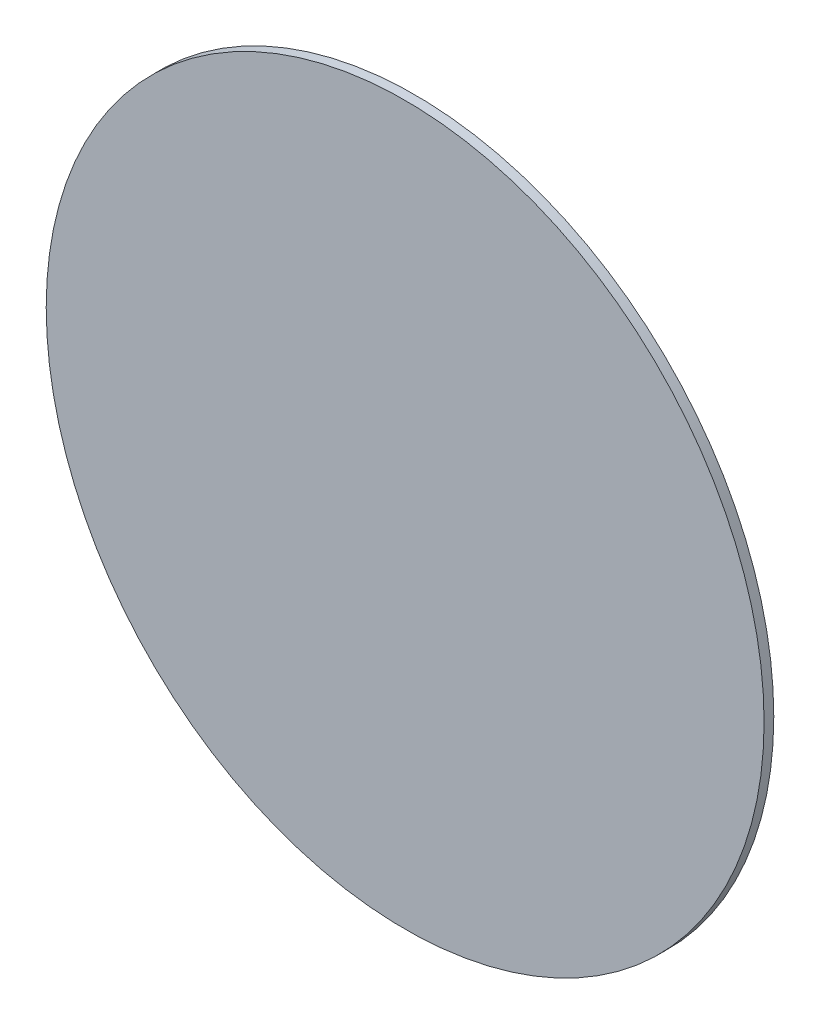
SolidWorks part; units mm, degrees
ref_plane "Front Plane" through (0, 0, 0) normal (0, 0, 1) x (1, 0, 0)
ref_plane "Top Plane" through (0, 0, 0) normal (0, 1, 0) x (1, 0, 0)
ref_plane "Right Plane" through (0, 0, 0) normal (1, 0, 0) x (0, 0, -1)
sketch "Sketch1" plane through (0, 0, 0) normal (0, 0, 1) x (1, 0, 0)
  circle A0 centre (0, 0) radius 37
  dimension "D1" = 74
extrude "Boss-Extrude1" add sketch "Sketch1" along normal blind 1
